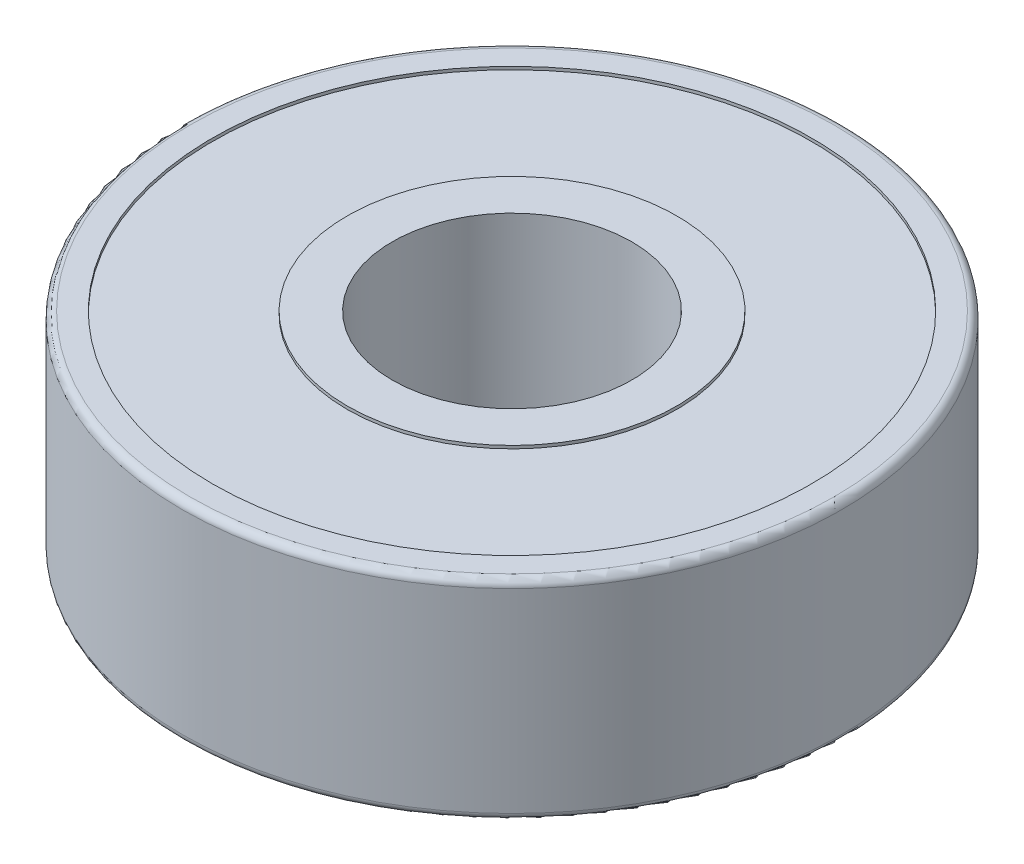
SolidWorks part; units mm, degrees
ref_plane "Front Plane" through (0, 0, 0) normal (0, 0, 1) x (1, 0, 0)
ref_plane "Top Plane" through (0, 0, 0) normal (0, 1, 0) x (1, 0, 0)
ref_plane "Right Plane" through (0, 0, 0) normal (1, 0, 0) x (0, 0, -1)
sketch "Sketch1" plane through (0, 0, 0) normal (0, 1, 0) x (1, 0, 0)
  circle A0 centre (0, 0) radius 11
  circle A1 centre (0, 0) radius 4
  dimension "D1" = 22
  dimension "D2" = 8
extrude "Boss-Extrude1" add sketch "Sketch1" along normal blind 7
sketch "Sketch2" plane through (0, 7, 0) normal (0, 1, 0) x (1, 0, 0)
  circle A0 centre (0, 0) radius 4 construction
  circle A1 centre (0, 0) radius 11
  circle A2 centre (0, 0) radius 11 construction
  circle A3 centre (0, 0) radius 4 construction
  circle A4 centre (0, 0) radius 10
  circle A5 centre (0, 0) radius 5.5
  dimension "D1" = 0
  dimension "D2" = 1
  dimension "D3" = 1.5
extrude "Cut-Extrude1" cut sketch "Sketch2" against normal blind 0.1
ref_plane "Plane1" through (0, 3.5, 0) normal (0, 1, 0) x (1, 0, 0)
mirror "Mirror1" about plane through (0, 3.5, 0) normal (0, 1, 0) of "Cut-Extrude1"
fillet "Fillet1" radius 0.25 2 edges at (0, 7, 11) (0, 0, 11)
